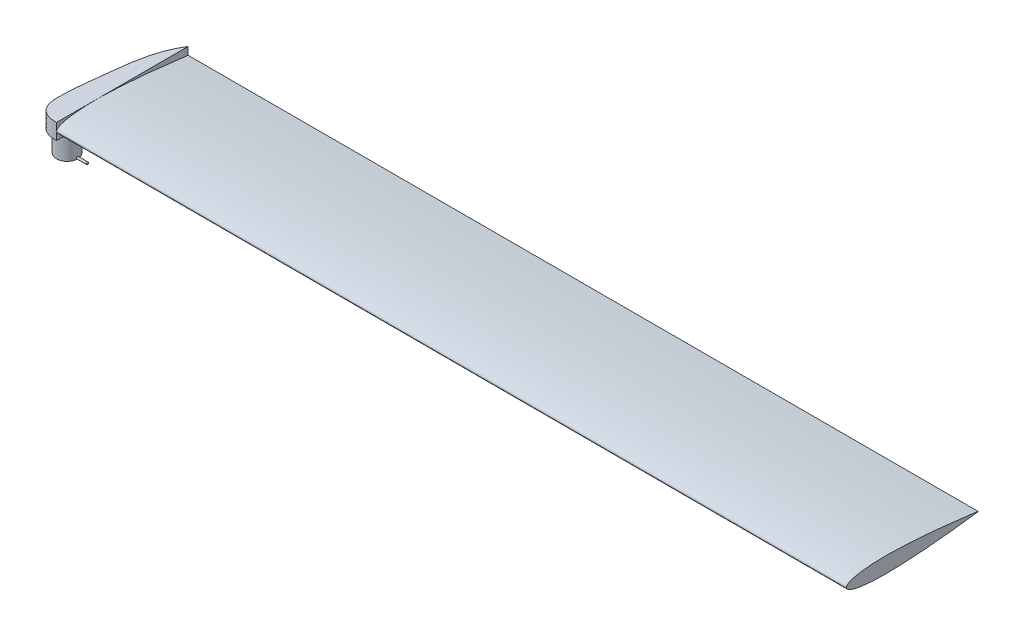
SolidWorks part; units mm, degrees
ref_plane "Ön Düzlem" through (0, 0, 0) normal (0, 0, 1) x (1, 0, 0)
ref_plane "Üst Düzlem" through (0, 0, 0) normal (0, 1, 0) x (1, 0, 0)
ref_plane "Sağ Düzlem" through (0, 0, 0) normal (1, 0, 0) x (0, 0, -1)
sketch "Sketch1" plane through (0, 0, 0) normal (1, 0, 0) x (0, 0, -1)
  line L0 (305.5, 117) -> (1527.5, 117) construction
  line L1 (124.9958, 7.6975) -> (124.9958, 7.3551)
  spline S0 degree 3 poles (124.9958, 7.6975) (121.5494, 8.133) (115.7079, 8.8711) (106.6128, 10.0012) (98.7767, 10.9001) (91.0104, 11.7181) (84.4662, 12.3744) (77.1231, 13.0109) (70.0969, 13.6616) (63.2322, 14.0383) (56.9512, 14.4586) (50.1831, 14.7448) (43.7131, 14.9288) (38.0167, 14.9868) (31.8671, 14.9642) (25.9611, 14.7642) (20.4185, 14.3189) (16.0809, 13.9021) (11.9484, 13.2767) (7.872, 12.4387) (4.5515, 11.4816) (1.9351, 10.1896) (0.4198, 8.8678) (-0.1163, 7.6764) (0.2285, 6.5757) (1.0921, 5.3828) (3.1213, 4.1827) (5.8339, 3.1224) (8.9694, 2.338) (12.4549, 1.6356) (16.398, 1.0576) (20.4074, 0.6193) (24.9405, 0.3185) (28.9969, 0.0979) (33.6404, 0.065) (37.6198, -0.0088) (42.1302, 0.0152) (46.8255, 0.1281) (52.0592, 0.3082) (57.5703, 0.566) (63.0666, 0.9035) (68.7816, 1.2736) (74.2411, 1.7012) (79.3321, 2.132) (83.7651, 2.5258) (88.3339, 3.015) (93.4519, 3.4955) (98.4485, 4.0307) (103.3599, 4.5597) (107.5347, 5.0511) (112.036, 5.6526) (116.8989, 6.2051) (121.1853, 6.8982) (124.0349, 7.1356) (124.8716, 7.3267) (124.9958, 7.3551) knots 0 0 0 0 0.04091 0.069341 0.107932 0.133796 0.161307 0.185386 0.220598 0.244394 0.266344 0.294731 0.324163 0.342565 0.361816 0.396586 0.412117 0.427295 0.447896 0.461301 0.476285 0.488528 0.495262 0.499816 0.502761 0.50837 0.516837 0.529992 0.542689 0.554812 0.57187 0.589596 0.602296 0.625369 0.637421 0.656977 0.672241 0.690534 0.712285 0.733913 0.755504 0.777134 0.801357 0.819993 0.837304 0.853767 0.874103 0.897841 0.912946 0.932278 0.947342 0.966429 0.989896 0.9985 1 1 1 1
extrude "Boss-Extrude1" add sketch "Sketch1" along normal blind 750
sketch "Sketch2" plane through (0, 0, 0) normal (0, 1, 0) x (1, 0, 0)
  line L0 (0, 124.9958) -> (0, -0.0001)
  line L3 (375, 257.3253) -> (375, -119.6644) construction
  circle A4 centre (-10, 19.9999) radius 10
  spline S0 degree 2 poles (0, -0.0001) (-19.65, -0.3381) (-20, 19.9999) knots 0 0 0 1 1 1
  spline S1 degree 3 poles (-20, 19.9999) (-20.2565, 33.6052) (-15.1417, 69.221) (-12.6667, 105.0115) (0, 124.9958) knots 0 0 0 0 0.363919 1 1 1 1
extrude "Boss-Extrude2" add sketch "Sketch2" along normal blind 15 contours S1 A4 L0 | S0 A4 | S0 L0 A4
sketch "Sketch3" plane through (0, 0, 0) normal (0, -1, 0) x (1, 0, 0)
  line L0 (0, -124.9958) -> (0, 0.0001) construction
  circle A0 centre (-10, -19.9999) radius 10
  dimension "D1" = 20
  dimension "D2" = 20
extrude "Boss-Extrude4" add sketch "Sketch3" along normal blind 25 contours A0
sketch "Sketch4" plane through (0, 0, 0) normal (1, 0, 0) x (0, 0, -1)
  line L0 (29.9999, -25) -> (29.9999, 0) construction
  line L1 (9.9999, -25) -> (29.9999, -25) construction
  circle A0 centre (19.9999, -24) radius 1
  dimension "D1" = 2
  dimension "D2" = 10
extrude "Boss-Extrude5" add sketch "Sketch4" along normal blind 9.5 and the other way up to next
